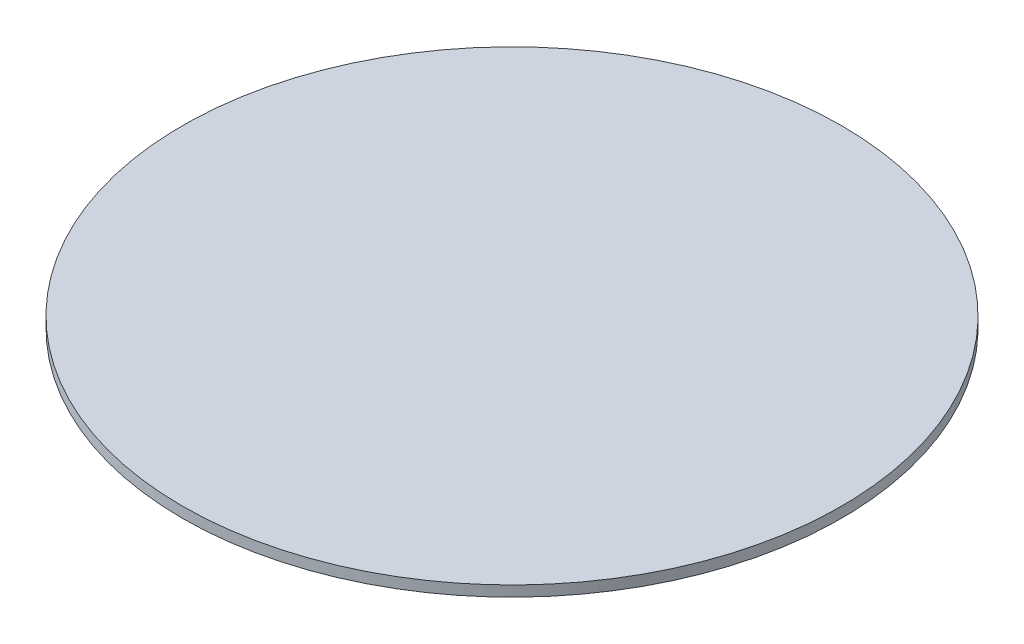
SolidWorks part; units mm, degrees
ref_plane "Front Plane" through (0, 0, 0) normal (0, 0, 1) x (1, 0, 0)
ref_plane "Top Plane" through (0, 0, 0) normal (0, 1, 0) x (1, 0, 0)
ref_plane "Right Plane" through (0, 0, 0) normal (1, 0, 0) x (0, 0, -1)
sketch "Sketch1" plane through (0, 0, 0) normal (0, 1, 0) x (1, 0, 0)
  circle A0 centre (0, 0) radius 9.35
  dimension "D1" = 18.7
extrude "Boss-Extrude1" add sketch "Sketch1" along normal blind 0.3
